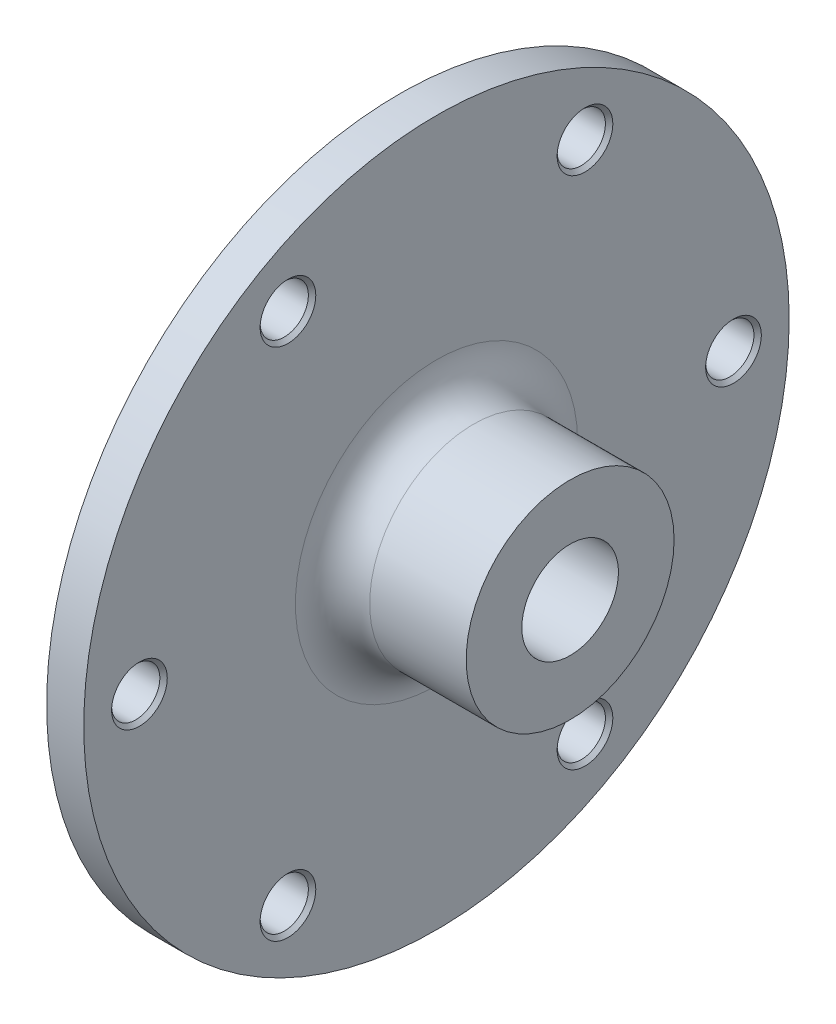
SolidWorks part; units mm, degrees
ref_plane "Front Plane" through (0, 0, 0) normal (0, 0, 1) x (1, 0, 0)
ref_plane "Top Plane" through (0, 0, 0) normal (0, 1, 0) x (1, 0, 0)
ref_plane "Right Plane" through (0, 0, 0) normal (1, 0, 0) x (0, 0, -1)
sketch "Sketch1" plane through (0, 0, 0) normal (0, 0, 1) x (1, 0, 0)
  line L0 (0, 0) -> (-28, 0)
  line L1 (-28, 0) -> (-28, 35)
  line L2 (-28, 35) -> (-23, 35)
  line L3 (-23, 35) -> (-23, 47.5)
  line L4 (-23, 47.5) -> (-18, 47.5)
  line L5 (-18, 47.5) -> (-18, 14)
  line L6 (-18, 14) -> (0, 14)
  line L7 (0, 14) -> (0, 0)
  dimension "D1" = 28
  dimension "D2" = 14
  dimension "D3" = 47.5
  dimension "D4" = 35
  dimension "D5" = 5
  dimension "D6" = 5
revolve "Revolve1" add sketch "Sketch1" angle 360 about L0
fillet "Fillet1" radius 5 1 edges at (-18, 0, -14)
hole_wizard "CSK for M12 Hex Socket Countersunk Cap Screw1" positions "Sketch2" profile "Sketch3" countersink size "M12" standard "ISO" end condition through all
sketch "Sketch2" plane through (-28, 0, 0) normal (-1, 0, 0) x (0, 0, 1)
  point P0 (0, 0)
sketch "Sketch3" plane through (-28, 0, 0) normal (0, 1, 0) x (0, 0, 1)
  line L0 (0, 0) -> (0, 28)
  line L1 (0, 28) -> (6.5, 28)
  line L2 (6.5, 28) -> (6.5, 6.5)
  line L3 (6.5, 6.5) -> (13, 0)
  line L5 (13, 0) -> (0, 0)
  line L6 (-6.5, 6.5) -> (-13, 0) construction
  line L11 (0, -6.35) -> (0, 107.95) construction
  dimension "Thru Hole Dia." = 13
  dimension "Thru Hole Depth" = 28
  dimension "Near C'Sink Dia." = 26
  dimension "Near C'Sink Angle" = 90
sketch "Sketch4" plane through (-18, 0, 0) normal (1, 0, 0) x (0, 0, -1)
  circle A0 centre (0, 0) radius 40 construction
  dimension "D1" = 80
hole_wizard "CSK for M6 Hex Socket Countersunk Cap Screw1" positions "Sketch5" profile "Sketch6" countersink size "M6" standard "ISO" end condition through all
sketch "Sketch5" plane through (-18, 0, 0) normal (1, 0, 0) x (0, 0, -1)
  circle A0 centre (0, 0) radius 40 construction
  point P0 (-40, 0)
sketch "Sketch6" plane through (-18, 0, 40) normal (0, 1, 0) x (0, 0, -1)
  line L0 (0, 0) -> (0, 10)
  line L1 (0, 10) -> (3.25, 10)
  line L2 (3.25, 10) -> (3.25, 0.5)
  line L3 (3.25, 0.5) -> (3.75, 0)
  line L5 (3.75, 0) -> (0, 0)
  line L6 (-3.25, 0.5) -> (-3.75, 0) construction
  line L11 (0, -6.35) -> (0, 107.95) construction
  dimension "Thru Hole Dia." = 6.5
  dimension "Thru Hole Depth" = 10
  dimension "Near C'Sink Dia." = 7.5
  dimension "Near C'Sink Angle" = 90
pattern_circular "CirPattern1" count 6 over 360 about axis through (0, 0, 0) along (1, 0, 0) of "CSK for M6 Hex Socket Countersunk Cap Screw1"
